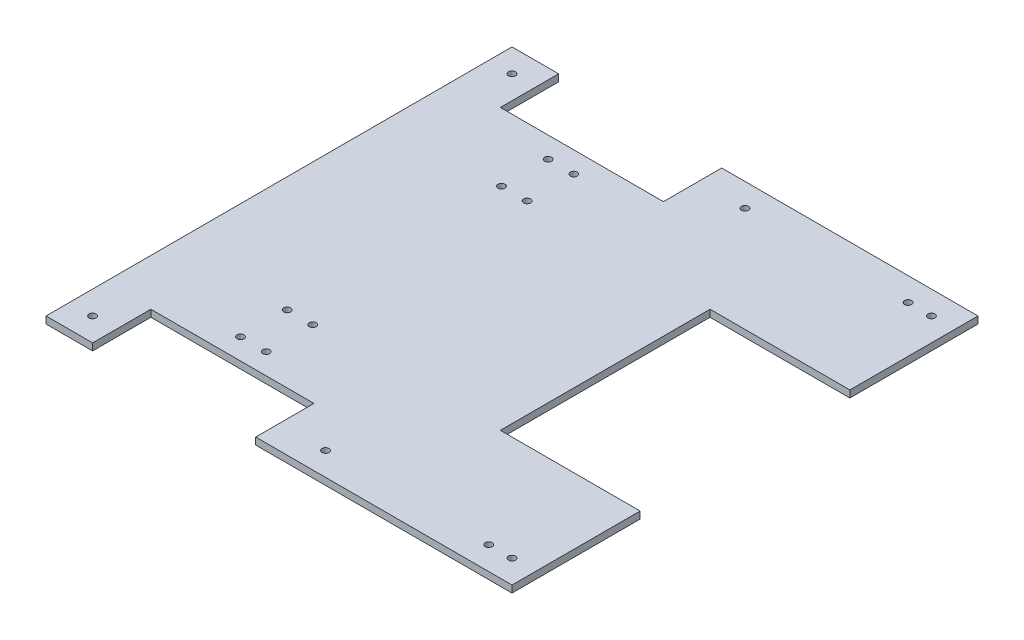
SolidWorks part; units mm, degrees
material "Acrylic (Medium-high impact)"
ref_plane "Front Plane" through (0, 0, 0) normal (0, 0, 1) x (1, 0, 0)
ref_plane "Top Plane" through (0, 0, 0) normal (0, 1, 0) x (1, 0, 0)
ref_plane "Right Plane" through (0, 0, 0) normal (1, 0, 0) x (0, 0, -1)
sketch "Sketch1" plane through (0, 0, 0) normal (0, 1, 0) x (1, 0, 0)
  line L0 (-20, -130) -> (0, -130)
  line L1 (0, -130) -> (0, -105)
  line L2 (0, -105) -> (70, -105)
  line L3 (70, -105) -> (70, -130)
  line L4 (70, -130) -> (180, -130)
  line L5 (180, -130) -> (180, 70)
  line L6 (180, 70) -> (70, 70)
  line L7 (70, 70) -> (70, 45)
  line L8 (70, 45) -> (0, 45)
  line L9 (0, 45) -> (0, 70)
  line L10 (0, 70) -> (-20, 70)
  line L11 (-20, 70) -> (-20, -130)
  dimension "D1" = 70
  dimension "D2" = 70
  dimension "D3" = 25
  dimension "D4" = 25
  dimension "D5" = 25
  dimension "D6" = 25
  dimension "D7" = 20
  dimension "D8" = 20
  dimension "D9" = 200
  dimension "D10" = 110
  dimension "D11" = 0
  dimension "D12" = 45
extrude "Boss-Extrude1" add sketch "Sketch1" along normal blind 3
sketch "Sketch2" plane through (0, 3, 0) normal (0, 1, 0) x (1, 0, 0)
  line L0 (0, -105) -> (70, -105) construction
  line L1 (35, -105) -> (35, 45) construction
  line L2 (70, 45) -> (0, 45) construction
  line L3 (35, -30) -> (-20, -30) construction
  line L4 (-20, 70) -> (-20, -130) construction
  circle A0 centre (29.5, -96) radius 1.5
  circle A1 centre (29.5, -76) radius 1.5
  circle A2 centre (40.5, -96) radius 1.5
  circle A3 centre (40.5, -76) radius 1.5
  circle A4 centre (29.5, 36) radius 1.5
  circle A5 centre (40.5, 36) radius 1.5
  circle A6 centre (40.5, 16) radius 1.5
  circle A7 centre (29.5, 16) radius 1.5
  point P6 (35, -105)
  dimension "D1" = 3
  dimension "D4" = 3
  dimension "D2" = 9
  dimension "D3" = 5.5
  dimension "D5" = 20
  dimension "D6" = 5.5
extrude "Cut-Extrude1" cut sketch "Sketch2" against normal blind 3
sketch "Sketch3" plane through (0, 3, 0) normal (0, 1, 0) x (1, 0, 0)
  line L0 (-20, -30) -> (180, -30) construction
  line L1 (-20, 70) -> (-20, -130) construction
  line L2 (180, -130) -> (180, 70) construction
  line L3 (-20, -130) -> (0, -130) construction
  line L4 (70, -130) -> (180, -130) construction
  circle A0 centre (-10, -120) radius 1.5
  circle A1 centre (160, -120) radius 1.5
  circle A2 centre (160, 60) radius 1.5
  circle A3 centre (-10, 60) radius 1.5
  dimension "D1" = 3
  dimension "D4" = 3
  dimension "D2" = 10
  dimension "D3" = 10
  dimension "D5" = 20
  dimension "D6" = 10
sketch "Sketch4" plane through (180, 0, 0) normal (1, 0, 0) x (0, 0, -1)
  line L0 (-30, 3) -> (-30, 0) construction
  line L1 (-130, 3) -> (70, 3) construction
  line L2 (-130, 0) -> (70, 0) construction
sketch "Sketch5" plane through (-20, 0, 0) normal (-1, 0, 0) x (0, 0, 1)
  line L0 (30, 3) -> (30, 0) construction
  line L1 (-70, 3) -> (130, 3) construction
  line L2 (-70, 0) -> (130, 0) construction
sketch "Sketch6" plane through (0, 3, 0) normal (0, 1, 0) x (1, 0, 0)
  line L0 (180, -130) -> (180, 70) construction
  line L1 (70, -130) -> (180, -130) construction
  line L2 (180, -30) -> (-20, -30) construction
  line L3 (80, -130) -> (80, 70) construction
  line L4 (180, 70) -> (70, 70) construction
  line L5 (130, 70) -> (130, -130) construction
  circle A0 centre (170, -120) radius 1.5
  circle A1 centre (170, 60) radius 1.5
  circle A2 centre (90, -120) radius 1.5
  circle A3 centre (90, 60) radius 1.5
  dimension "D1" = 3
  dimension "D2" = 10
  dimension "D3" = 10
  dimension "D4" = 100
  dimension "D5" = 50
extrude "Cut-Extrude2" cut sketch "Sketch6" against normal blind 3
sketch "Sketch8" plane through (0, 3, 0) normal (0, 1, 0) x (1, 0, 0)
  line L0 (180, -130) -> (180, 70) construction
  line L1 (180, 15) -> (120, 15)
  line L2 (180, 15) -> (180, -75)
  line L3 (180, -75) -> (120, -75)
  line L4 (120, 15) -> (120, -75)
  line L5 (-20, -30) -> (180, -30) construction
  dimension "D1" = 60
  dimension "D2" = 90
  dimension "D3" = 45
extrude "Cut-Extrude4" cut sketch "Sketch8" against normal blind 3
extrude "Cut-Extrude5" cut sketch "Sketch3" against normal blind 3
